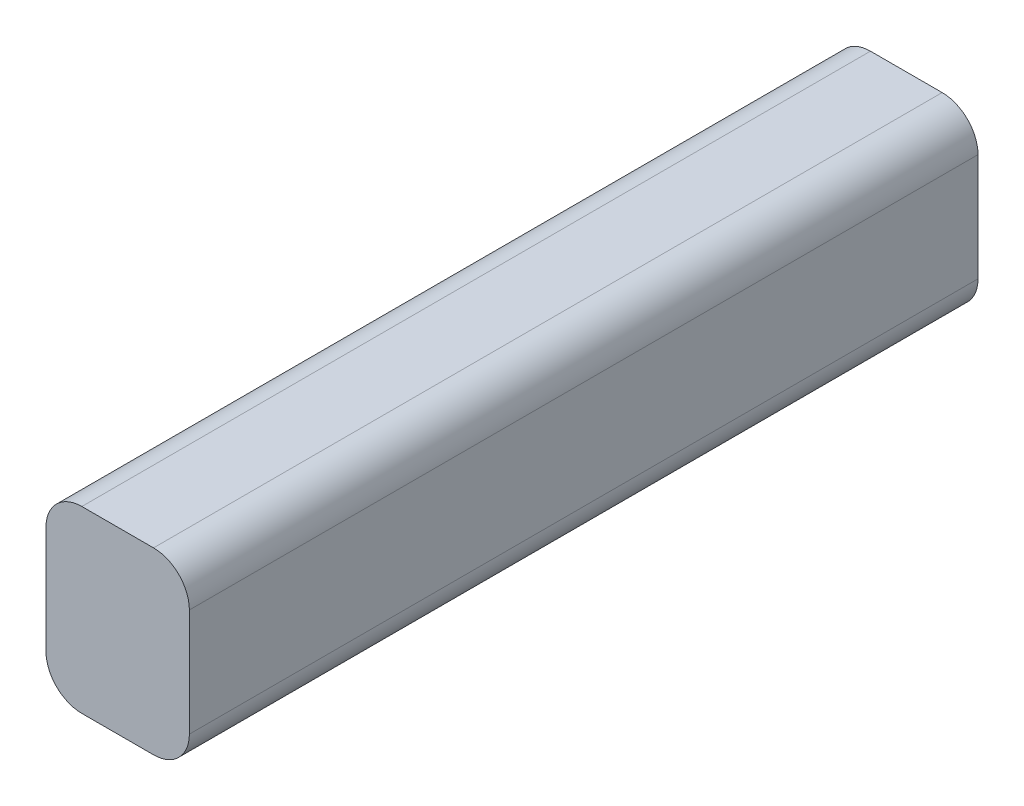
SolidWorks part; units mm, degrees
ref_plane "Front Plane" through (0, 0, 0) normal (0, 0, 1) x (1, 0, 0)
ref_plane "Top Plane" through (0, 0, 0) normal (0, 1, 0) x (1, 0, 0)
ref_plane "Right Plane" through (0, 0, 0) normal (1, 0, 0) x (0, 0, -1)
sketch "Sketch1" plane through (0, 0, 0) normal (0, 0, 1) x (1, 0, 0)
  line L1 (-100, 125) -> (100, 125)
  line L2 (-100, 125) -> (-100, -125)
  line L3 (-100, -125) -> (100, -125)
  line L4 (100, 125) -> (100, -125)
  line L5 (-100, 125) -> (100, -125) construction
  line L6 (-100, -125) -> (100, 125) construction
  point P0 (0, 0)
  dimension "D1" = 200
  dimension "D2" = 250
extrude "Boss-Extrude1" add sketch "Sketch1" along normal blind 1100
fillet "Fillet1" radius 50 1 edges at (-100, 125, 550)
fillet "Fillet2" radius 50 1 edges at (-100, -125, 550)
fillet "Fillet3" radius 50 1 edges at (100, 125, 550)
fillet "Fillet4" radius 50 1 edges at (100, -125, 550)
sketch "Sketch2" plane through (0, 0, 1100) normal (0, 0, 1) x (1, 0, 0)
  line L0 (-100, 75) -> (100, 75) construction
  line L1 (100, 75) -> (100, -75) construction
  line L2 (0, 75) -> (0, 125)
  line L3 (50, 125) -> (-50, 125) construction
sketch "Sketch3" plane through (0, 0, 1100) normal (0, 0, 1) x (1, 0, 0)
  line L0 (-9.855, 125) -> (-9.855, 124.0358)
  line L1 (50, 125) -> (-50, 125) construction
